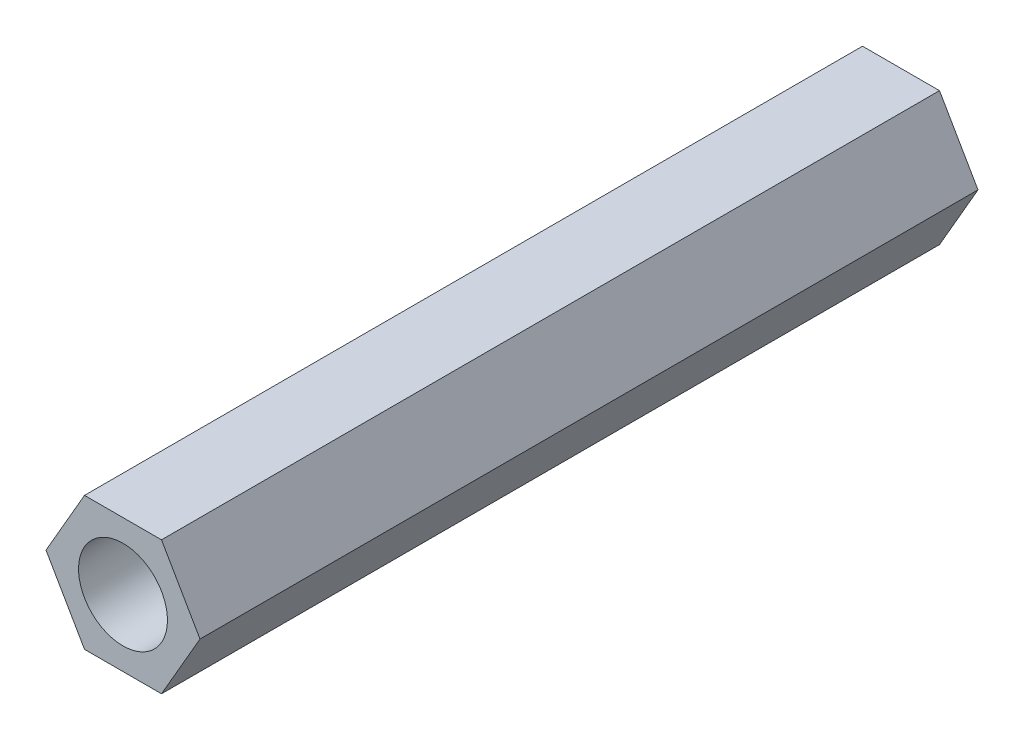
SolidWorks part; units mm, degrees
material "普通碳钢"
ref_plane "前视基准面" through (0, 0, 0) normal (0, 0, 1) x (1, 0, 0)
ref_plane "上视基准面" through (0, 0, 0) normal (0, 1, 0) x (1, 0, 0)
ref_plane "右视基准面" through (0, 0, 0) normal (1, 0, 0) x (0, 0, -1)
sketch "草图1" plane through (0, 0, 0) normal (0, 0, 1) x (1, 0, 0)
  line L1 (3.4641, 0) -> (1.7321, 3)
  line L2 (1.7321, 3) -> (-1.7321, 3)
  line L3 (-1.7321, 3) -> (-3.4641, 0)
  line L4 (-3.4641, 0) -> (-1.7321, -3)
  line L5 (-1.7321, -3) -> (1.7321, -3)
  line L6 (1.7321, -3) -> (3.4641, 0)
  circle A0 centre (0, 0) radius 3 construction
  circle A1 centre (0, 0) radius 2
  dimension "D1" = 6
  dimension "D2" = 4
extrude "凸台-拉伸1" add sketch "草图1" along normal blind 35
cosmetic thread "装饰螺纹线1"
